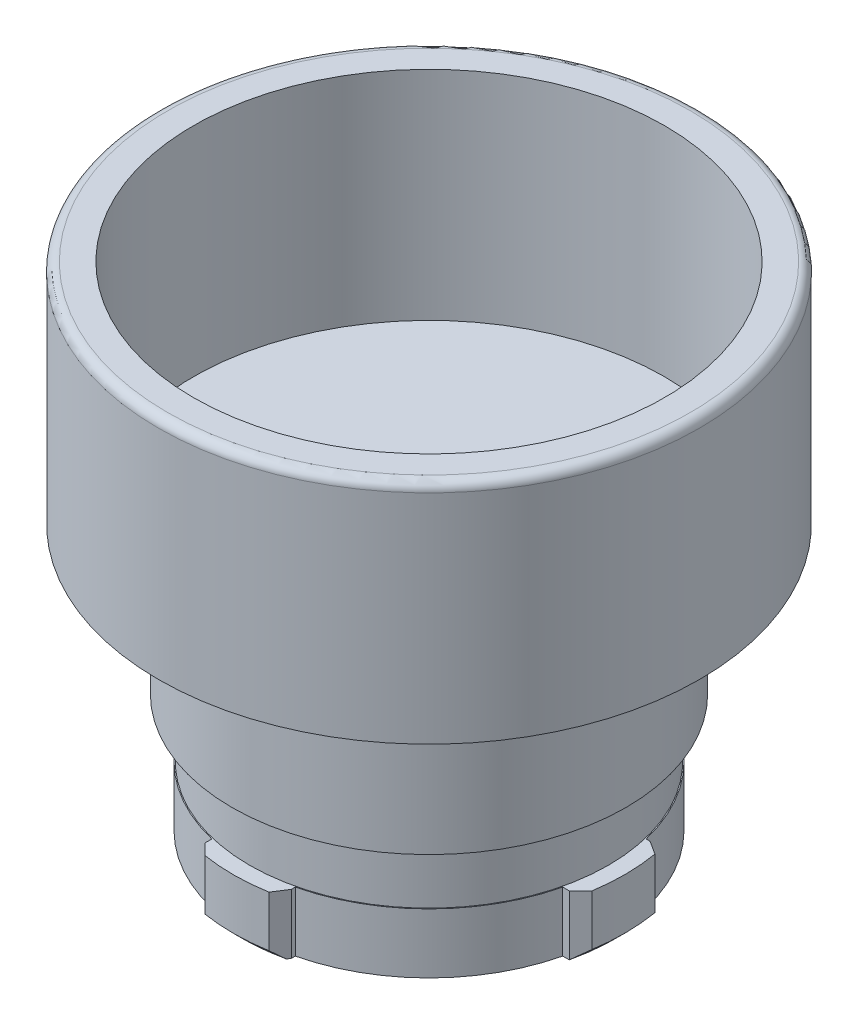
SolidWorks part; units mm, degrees
material "Alloy Steel"
ref_plane "Front Plane" through (0, 0, 0) normal (0, 0, 1) x (1, 0, 0)
ref_plane "Top Plane" through (0, 0, 0) normal (0, 1, 0) x (1, 0, 0)
ref_plane "Right Plane" through (0, 0, 0) normal (1, 0, 0) x (0, 0, -1)
ref_plane "Plane1" through (0, -3.3, 0) normal (0, -1, 0) x (1, 0, 0)
sketch "Sketch1" plane through (0, -3.3, 0) normal (0, -1, 0) x (1, 0, 0)
  line L0 (-2.3, 10.0523) -> (-2.3, 9.6805)
  line L1 (-9.6805, 2.3) -> (-9.8979, 2.3)
  line L2 (-9.8979, 2.3) -> (-10.6456, 1.8199)
  line L3 (-10.6678, -1.6844) -> (-10.0523, -2.3)
  line L4 (-10.0523, -2.3) -> (-9.6805, -2.3)
  line L5 (-2.3, -9.6805) -> (-2.3, -9.8979)
  line L6 (-2.3, -9.8979) -> (-1.8199, -10.6456)
  line L7 (1.6844, -10.6678) -> (2.3, -10.0523)
  line L8 (2.3, -10.0523) -> (2.3, -9.6805)
  line L9 (9.6805, -2.3) -> (9.8979, -2.3)
  line L10 (9.8979, -2.3) -> (10.6456, -1.8199)
  line L11 (10.6678, 1.6844) -> (10.0523, 2.3)
  line L12 (10.0523, 2.3) -> (9.6805, 2.3)
  line L13 (2.3, 9.6805) -> (2.3, 9.8979)
  line L14 (2.3, 9.8979) -> (1.8199, 10.6456)
  line L15 (-1.6844, 10.6678) -> (-2.3, 10.0523)
  arc A0 (-2.3, 9.6805) -> (-9.6805, 2.3) centre (0, 0) ccw
  arc A1 (-10.6456, 1.8199) -> (-10.6678, -1.6844) centre (0, 0) ccw
  arc A2 (-9.6805, -2.3) -> (-2.3, -9.6805) centre (0, 0) ccw
  arc A3 (-1.8199, -10.6456) -> (1.6844, -10.6678) centre (0, 0) ccw
  arc A4 (2.3, -9.6805) -> (9.6805, -2.3) centre (0, 0) ccw
  arc A5 (10.6456, -1.8199) -> (10.6678, 1.6844) centre (0, 0) ccw
  arc A6 (9.6805, 2.3) -> (2.3, 9.6805) centre (0, 0) ccw
  arc A7 (1.8199, 10.6456) -> (-1.6844, 10.6678) centre (0, 0) ccw
extrude "Boss-Extrude1" add sketch "Sketch1" against normal blind 3.3
sketch "Sketch2" plane through (0, 0, 0) normal (0, 0, 1) x (1, 0, 0)
  line L0 (14.925, 23.9) -> (0, 23.9)
  line L1 (0, 23.9) -> (0, 0)
  line L2 (0, 0) -> (9.9, 0)
  line L3 (9.9, 0) -> (9.9, 3.25)
  line L4 (9.9, 3.25) -> (10.875, 3.25)
  line L5 (10.875, 3.25) -> (10.875, 10.05)
  line L6 (10.875, 10.05) -> (12, 10.05)
  line L7 (12, 10.05) -> (12, 11.39)
  line L8 (12, 11.39) -> (14.925, 11.39)
  line L9 (14.925, 11.39) -> (14.925, 23.9)
  line L10 (0, 23.9) -> (0, 0) construction
revolve "Revolve1" add sketch "Sketch2" angle 360 about L10
hole_wizard "M22 Clearance Hole1" positions "Sketch4" profile "Sketch3" hole size "M22" standard "ANSI Metric"
sketch "Sketch4" plane through (0, 23.9, 0) normal (0, 1, 0) x (1, 0, 0)
  point P0 (0, 0)
sketch "Sketch3" plane through (0, 23.9, 0) normal (1, 0, 0) x (0, 0, 1)
  line L0 (0, 0) -> (0, 12)
  line L1 (0, 12) -> (13, 12)
  line L2 (13, 12) -> (13, 0)
  line L5 (13, 0) -> (0, 0)
  line L10 (0, 12) -> (-13, 12) construction
  line L11 (0, -6.35) -> (0, 107.95) construction
  dimension "Hole Dia." = 26
  dimension "Hole Depth" = 12
  dimension "Drill Angle" = 180
chamfer "Chamfer1" distance 0.5 angle 45 4 edges at (-10.7998, -3.3, 0.0687) (0.0687, -3.3, 10.7998) (-0.0687, -3.3, -10.7998) (10.7998, -3.3, -0.0687)
fillet "Fillet1" radius 0.5 1 edges at (0, 23.9, -14.925)
